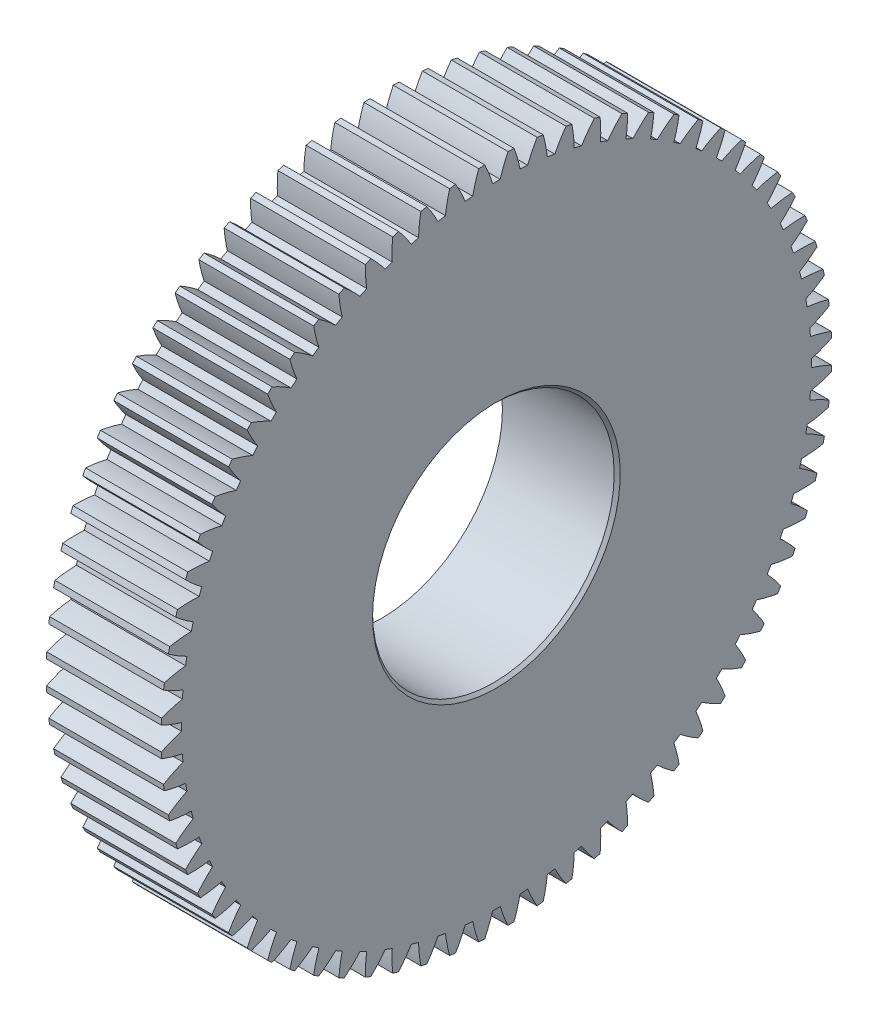
SolidWorks part; units mm, degrees
ref_plane "Plane1" through (0, 0, 0) normal (0, 0, 1) x (1, 0, 0)
ref_plane "Plane2" through (0, 0, 0) normal (0, 1, 0) x (1, 0, 0)
ref_plane "Plane3" through (0, 0, 0) normal (1, 0, 0) x (0, 0, -1)
sketch "HoldingSke" plane through (0, 0, 0) normal (0, 1, 0) x (1, 0, 0)
  line L0 (0, 0) -> (0.103, -0.317)
  line L1 (-15, 0) -> (100, 0) construction
  line L2 (0, 0) -> (-2.1039, 2.3779)
  line L3 (0, 0) -> (-11.863, 4.5341)
  line L4 (0, 0) -> (2.6687, 8.2133)
  line L5 (0, 0) -> (-46.8476, -17.4728)
  line L6 (0, 0) -> (-31.5006, -21.2535)
  line L7 (-2.1039, 2.3779) -> (8.6586, 51.2059)
  line L8 (-76.2, 54.61) -> (-70.8, 54.61)
  line L9 (-71.009, 38.7566) -> (-53.1078, 45.2721)
  line L10 (-76.2, 71.12) -> (104.1128, 71.12)
  line L11 (0, 0) -> (-38, 0)
  line L12 (-76.2, 101.6) -> (-76.093, 101.6)
  line L13 (24.9733, 27.94) -> (52.9518, 28.4284)
  line L14 (24.9733, 27.94) -> (24.9743, 27.94)
  line L15 (24.9733, 27.94) -> (100.4006, 29.5858)
  line L16 (-63.627, -3) -> (-12.827, -3)
  circle A0 centre (0, 0) radius 40
  circle A1 centre (0, 0) radius 37.5
  circle A2 centre (0, 0) radius 37.5
  circle A3 centre (0, 0) radius 40
  dimension "MHD" = 75
  dimension "Hub_dia" = 75
  dimension "Bore" = 80
  dimension "MBD" = 80
  dimension "Num_teeth" = 72
  dimension "Pitch" = 0.3333
  dimension "Overall_len" = 50
  dimension "Show_teeth" = 72
  dimension "Thickness" = 38
  dimension "OAL" = 50.0001
  dimension "T_dim" = 5.4
  dimension "Ap" = 20
  dimension "H" = 19.05
  dimension "Pitch_radius" = 180.3128
  dimension "Width" = 38
  dimension "Backlash" = 0.107
  dimension "Addendum_fac" = 1
  dimension "Dedendum_fac" = 1.25
  dimension "Clearance_fac" = 0.25
  dimension "Dedendum_add" = 0.001
  dimension "Module" = 3
sketch "BasProSke" plane through (0, 0, 0) normal (0, 1, 0) x (1, 0, 0)
  line L0 (-10, 0) -> (60, 0) construction
  line L1 (0, 0) -> (0, 111)
  line L2 (0, 0) -> (38, 0)
  line L3 (38, 0) -> (38, 111)
  line L4 (38, 111) -> (0, 111)
  dimension "Thickness" = 38
  dimension "Diameter" = 222
revolve "Base-Revolve" add sketch "BasProSke" angle 360 about L0
sketch "TooCutSke" plane through (0, 0, 0) normal (1, 0, 0) x (0, 0, -1)
  line L1 (0, 0) -> (0, 107) construction
  line L2 (0, 0) -> (-2.5433, 107.9701) construction
  line L3 (0, 0) -> (-9.4199, 215.7509) construction
  line L4 (-2.5433, 107.9701) -> (-4.7099, 107.8755) construction
  arc A0 (1.2601, 104.2414) -> (-1.2601, 104.2414) centre (0, 0) ccw
  arc A1 (3.8595, 110.9583) -> (-3.8595, 110.9583) centre (0, 0) ccw
  circle A2 centre (0, 0) radius 108 construction
  circle A3 centre (0, 0) radius 101.4868 construction
  arc A4 (-1.2601, 104.2414) -> (-3.8595, 110.9583) centre (-42.708, 92.063) ccw
  arc A5 (3.8595, 110.9583) -> (1.2601, 104.2414) centre (42.708, 92.063) ccw
  dimension "Root_dia" = 208.498
  dimension "Overcut_dia" = 222.0508
  dimension "Pitch_dia" = 216
  dimension "Base_dia" = 202.9736
  dimension "Flank_rad" = 43.2
  dimension "Half_ang" = 2.5
  dimension "Half_CT" = 2.1688
extrude "ToothCut" cut sketch "TooCutSke" along normal through all
fillet "Breaks" [suppressed] radius 0.06
fillet "RootFillets" [suppressed] radius 0.751
pattern_circular "TeethCuts" count 72 over 360 about axis through (0, 0, 0) along (1, 0, 0) of "ToothCut", "RootFillets", "Breaks"
sketch "HubNeaOneSke" plane through (0, 0, 0) normal (-1, 0, 0) x (0, 0, 1)
  circle A0 centre (0, 0) radius 37.5
  dimension "Diameter" = 75
extrude "HubNearOne" [suppressed] add sketch "HubNeaOneSke" along normal blind 12.0001
sketch "HubNeaBotSke" plane through (0, 0, 0) normal (-1, 0, 0) x (0, 0, 1)
  circle A0 centre (0, 0) radius 37.5
  dimension "Diameter" = 75
extrude "HubNearBoth" [suppressed] add sketch "HubNeaBotSke" along normal blind 6
ref_plane "FarPln" through (38, 0, 0) normal (1, 0, 0) x (0, 0, -1)
sketch "HubFarSke" plane through (38, 0, 0) normal (1, 0, 0) x (0, 0, -1)
  circle A0 centre (0, 0) radius 37.5
  dimension "Diameter" = 75
extrude "HubFar" [suppressed] add sketch "HubFarSke" along normal blind 6
sketch "BorSke" plane through (0, 0, 0) normal (1, 0, 0) x (0, 0, -1)
  circle A0 centre (0, 0) radius 40
  dimension "Diameter" = 80
extrude "Bore" cut sketch "BorSke" along normal mid plane 100.0001
sketch "KeySke" plane through (0, 0, 0) normal (1, 0, 0) x (0, 0, -1)
  line L0 (-11, 0) -> (-11, 45.4)
  line L1 (-11, 45.4) -> (11, 45.4)
  line L2 (11, 45.4) -> (11, 0)
  line L3 (0, 0) -> (0, 34) construction
  line L4 (-11, 0) -> (11, 0)
  dimension "Offset" = 45.4
  dimension "Width" = 22
extrude "Keyway" [suppressed] cut sketch "KeySke" along normal mid plane 100.0001
pattern_circular "Keyway2" [suppressed] count 2 every 90 about axis through (-10, 0, 0) along (1, 0, 0)
chamfer "Smusso1" distance 1 angle 45 1 edges at (38, 0, 40)
equation "' \"Module@HoldingSke\" = 6.35"
equation "' \"Num_teeth@HoldingSke\" = 12"
equation "' \"Ap@HoldingSke\" =  20"
equation "' \"Ap@HoldingSke\" = 20"
equation "' \"Width@HoldingSke\" = 0.5 * 25.4"
equation "' \"Hub_dia@HoldingSke\"= 1 * 25.4"
equation "' \"Hub_dia@HoldingSke\" = 1 * 25.4"
equation "' \"Overall_len@HoldingSke\" = 1.0 * 25.4"
equation "' \"Bore@HoldingSke\" = 0.75 * 25.4"
equation "' \"T_dim@HoldingSke\" = 0.1 * 25.4"
equation "' \"Width@KeySke\" = 0.25 * 25.4"
equation "' \"Show_teeth@HoldingSke\" = 13"
equation "' \"Backlash@HoldingSke\" = 0.009 * 25.4"
equation "' \"Addendum_fac@HoldingSke\" = 1.0"
equation "' \"Dedendum_fac@HoldingSke\" = 1.25"
equation "' \"Dedendum_add@HoldingSke\" = 0.00005 * 25.4"
equation "' \"Clearance_fac@HoldingSke\" = 0.25"
equation "\"Pitch@HoldingSke\" = 1 / \"Module@HoldingSke\""
equation "\"Overcut_dia@TooCutSke\" = (\"Num_teeth@HoldingSke\" + 2 * \"Addendum_fac@HoldingSke\") / \"Pitch@HoldingSke\" + 0.002 * 25.4"
equation "\"Pitch_dia@TooCutSke\" = \"Num_teeth@HoldingSke\" / \"Pitch@HoldingSke\""
equation "\"Base_dia@TooCutSke\" = \"Num_teeth@HoldingSke\" / \"Pitch@HoldingSke\" * cos((\"Ap@HoldingSke\"  * 3.14159265 / 180))"
equation "\"Root_dia@TooCutSke\" = (\"Num_teeth@HoldingSke\" + 2) / \"Pitch@HoldingSke\" - 2 * (\"Addendum_fac@HoldingSke\" + \"Dedendum_fac@HoldingSke\") / \"Pitch@HoldingSke\" - \"Dedendum_add@HoldingSke\" * 2"
equation "\"Half_ang@TooCutSke\" = 180 / \"Num_teeth@HoldingSke\""
equation "\"Half_CT@TooCutSke\" = \"Num_teeth@HoldingSke\" / \"Pitch@HoldingSke\" * sin((3.14159265 / 2 / \"Num_teeth@HoldingSke\")) / 2 - 7 * \"Backlash@HoldingSke\" / 4"
equation "\"Flank_rad@TooCutSke\" = \"Num_teeth@HoldingSke\" / \"Pitch@HoldingSke\" / 5"
equation "\"Radius@RootFillets\" = \"Clearance_fac@HoldingSke\" / \"Pitch@HoldingSke\" + \"Dedendum_add@HoldingSke\""
equation "\"Break_rad@Breaks\" = 0.02 / \"Pitch@HoldingSke\""
equation "\"Thickness@HoldingSke\" = \"Width@HoldingSke\""
equation "\"OAL@HoldingSke\" = \"Thickness@HoldingSke\""
equation "\"MHD@HoldingSke\" = (\"Num_teeth@HoldingSke\" + 2) / \"Pitch@HoldingSke\" - 2 * (\"Addendum_fac@HoldingSke\" + \"Dedendum_fac@HoldingSke\")  / \"Pitch@HoldingSke\" - \"Dedendum_add@HoldingSke\" * 2"
equation "\"MBD@HoldingSke\" = (\"Num_teeth@HoldingSke\" + 2) / \"Pitch@HoldingSke\" - 2 * (\"Addendum_fac@HoldingSke\" + \"Dedendum_fac@HoldingSke\")  / \"Pitch@HoldingSke\" - \"Dedendum_add@HoldingSke\" * 2 - 0.002 * 25.4"
equation "\"MHD@HoldingSke\" = ((sgn( \"MHD@HoldingSke\" - \"Hub_dia@HoldingSke\" )-1)*( \"MHD@HoldingSke\" - \"Hub_dia@HoldingSke\" ))/-2+ \"Hub_dia@HoldingSke\""
equation "\"MBD@HoldingSke\" = ((sgn( \"MBD@HoldingSke\" - \"Bore@HoldingSke\" )-1)*( \"MBD@HoldingSke\" - \"Bore@HoldingSke\" ))/-2+ \"Bore@HoldingSke\""
equation "\"OAL@HoldingSke\" = ((sgn( \"OAL@HoldingSke\" - \"Overall_len@HoldingSke\" )+1)*( \"OAL@HoldingSke\" - \"Overall_len@HoldingSke\" ))/2 + \"Overall_len@HoldingSke\" + 0.000002 * 25.4"
equation "\"Num_teeth@TeethCuts\" = int( \"Show_teeth@HoldingSke\" ) + 1"
equation "\"Num_teeth@TeethCuts\" = ((sgn( \"Num_teeth@TeethCuts\" - \"Num_teeth@HoldingSke\" )-1)*( \"Num_teeth@TeethCuts\" - \"Num_teeth@HoldingSke\" ))/-2+ \"Num_teeth@HoldingSke\""
equation "\"Num_teeth@TeethCuts\" = ((sgn( \"Num_teeth@TeethCuts\" - 2.0)+1)*( \"Num_teeth@TeethCuts\" - 2.0))/2 +2.0"
equation "\"Angle@TeethCuts\" = 360.0 / \"Num_teeth@HoldingSke\""
equation "\"Diameter@BasProSke\" = (\"Num_teeth@HoldingSke\" + 2 * \"Addendum_fac@HoldingSke\") / \"Pitch@HoldingSke\""
equation "\"Thickness@BasProSke\"  = \"Thickness@HoldingSke\""
equation "' \"Fillet_rad@BasProSke\" =  \"Thickness@HoldingSke\" * 0.05"
equation "' \"Fillet_rad@BasProSke\" = \"Thickness@HoldingSke\" * 0.05"
equation "\"MHD@HoldingSke\" = ((sgn( \"MHD@HoldingSke\" - \"Root_dia@TooCutSke\" )-1)*( \"MHD@HoldingSke\" - \"Root_dia@TooCutSke\" ))/-2+ \"Root_dia@TooCutSke\""
equation "\"Diameter@HubNeaOneSke\" = \"MHD@HoldingSke\""
equation "\"Length@HubNearOne\" = \"OAL@HoldingSke\" - \"Thickness@BasProSke\""
equation "\"Diameter@HubNeaBotSke\" = \"MHD@HoldingSke\""
equation "\"Length@HubNearBoth\" = ( \"OAL@HoldingSke\" - \"Thickness@BasProSke\" ) / 2.0"
equation "\"Thickness@FarPln\" = \"Thickness@BasProSke\""
equation "\"Diameter@HubFarSke\" = \"MHD@HoldingSke\""
equation "\"Length@HubFar\" = ( \"OAL@HoldingSke\" - \"Thickness@BasProSke\" ) / 2.0"
equation "\"Diameter@BorSke\" = \"MBD@HoldingSke\""
equation "\"D1@Bore\" = \"OAL@HoldingSke\" * 2.0"
equation "\"D1@Keyway\" = \"OAL@HoldingSke\" * 2.0"
equation "\"Offset@KeySke\" = \"T_dim@HoldingSke\" + \"MBD@HoldingSke\" / 2.0"
